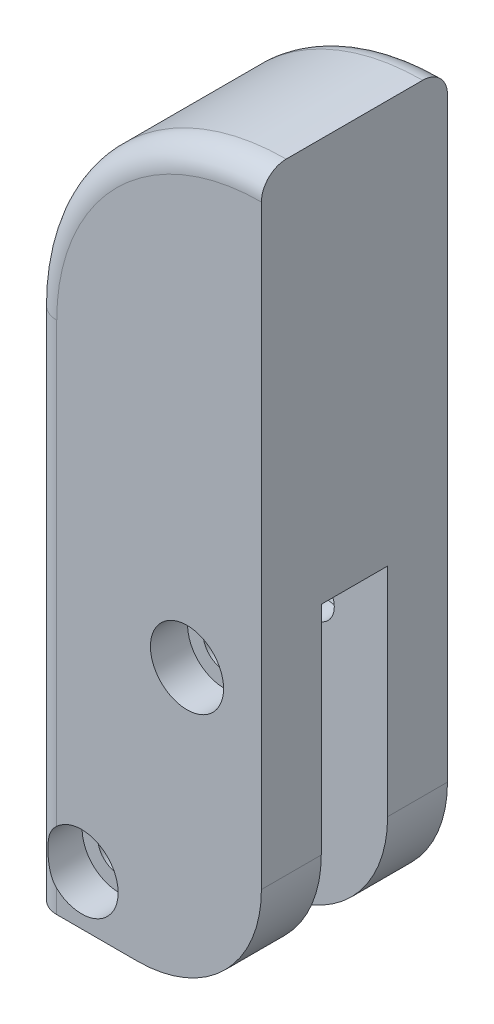
SolidWorks part; units mm, degrees
ref_plane "Alzado" through (0, 0, 0) normal (0, 0, 1) x (1, 0, 0)
ref_plane "Planta" through (0, 0, 0) normal (0, 1, 0) x (1, 0, 0)
ref_plane "Vista lateral" through (0, 0, 0) normal (1, 0, 0) x (0, 0, -1)
sketch "Croquis1" plane through (0, 0, 0) normal (0, 0, 1) x (1, 0, 0)
  line L1 (9.25, -20.75) -> (-9.25, -20.75)
  line L2 (9.25, -20.75) -> (9.25, 20.75)
  line L4 (-9.25, -20.75) -> (-9.25, 20.75)
  line L5 (9.25, -20.75) -> (-9.25, 20.75) construction
  line L6 (9.25, 20.75) -> (9.25, 39.25)
  arc A0 (9.25, 39.25) -> (-9.25, 20.75) centre (9.25, 20.75) ccw
  point P0 (0, 0)
  dimension "D1" = 60
  dimension "D2" = 18.5
extrude "Saliente-Extruir1" add sketch "Croquis1" along normal blind 15
sketch "Croquis2" plane through (9.25, 0, 0) normal (1, 0, 0) x (0, 0, -1)
  line L0 (-15, -20.75) -> (0, -20.75) construction
  line L1 (-10.175, 6.75) -> (-4.825, 6.75)
  line L2 (-10.175, 6.75) -> (-10.175, -20.75)
  line L3 (-10.175, -20.75) -> (-4.825, -20.75)
  line L4 (-4.825, 6.75) -> (-4.825, -20.75)
  line L5 (-10.175, 6.75) -> (-4.825, -20.75) construction
  line L6 (-10.175, -20.75) -> (-4.825, 6.75) construction
  point P0 (-7.5, -7)
  point P7 (-7.5, -20.75)
  dimension "D1" = 5.35
  dimension "D2" = 27.5
extrude "Cortar-Extruir1" cut sketch "Croquis2" against normal blind 30
sketch "Croquis3" plane through (0, 0, 15) normal (0, 0, 1) x (1, 0, 0)
  line L0 (-9.25, 20.75) -> (-9.25, -20.75) construction
  line L1 (-9.25, -20.75) -> (9.25, -20.75) construction
  circle A0 centre (3.25, 1.75) radius 1.7
  circle A1 centre (-5.25, -16.75) radius 1.7
  dimension "D5" = 3.4
  dimension "D1" = 4
  dimension "D2" = 4
  dimension "D3" = 22.5
  dimension "D4" = 12.5
extrude "Cortar-Extruir2" cut sketch "Croquis3" against normal blind 30
fillet "Redondeo1" radius 10 2 edges at (9.25, -20.75, 2.4125) (9.25, -20.75, 12.5875)
fillet "Redondeo2" radius 2 4 edges at (-9.25, 0, 0) (-3.8315, 33.8315, 0) (-9.25, 0, 15) (-3.8315, 33.8315, 15)
sketch "Croquis4" plane through (0, 0, 15) normal (0, 0, 1) x (1, 0, 0)
  circle A0 centre (3.25, 1.75) radius 2.95
  circle A1 centre (-5.25, -16.75) radius 2.95
  dimension "D1" = 5.9
extrude "Cortar-Extruir3" cut sketch "Croquis4" against normal blind 3
sketch "Croquis5" plane through (0, 0, 0) normal (0, 0, -1) x (-1, 0, 0)
  line L0 (-9.25, -10.75) -> (-9.25, 37.25) construction
  line L1 (-0.3488, 3.425) -> (-3.25, 5.1)
  line L2 (-3.25, 5.1) -> (-6.1512, 3.425)
  line L3 (-6.1512, 3.425) -> (-6.1512, 0.075)
  line L4 (-6.1512, 0.075) -> (-3.25, -1.6)
  line L5 (-3.25, -1.6) -> (-0.3488, 0.075)
  line L6 (-0.3488, 0.075) -> (-0.3488, 3.425)
  line L7 (5.25, -13.4) -> (2.3488, -15.075)
  line L8 (2.3488, -15.075) -> (2.3488, -18.425)
  line L9 (2.3488, -18.425) -> (5.25, -20.1)
  line L10 (5.25, -20.1) -> (8.1512, -18.425)
  line L11 (8.1512, -18.425) -> (8.1512, -15.075)
  line L12 (8.1512, -15.075) -> (5.25, -13.4)
  circle A0 centre (-3.25, 1.75) radius 3.35 construction
  circle A1 centre (5.25, -16.75) radius 3.35 construction
  dimension "D1" = 6.7
extrude "Cortar-Extruir4" cut sketch "Croquis5" against normal blind 3
